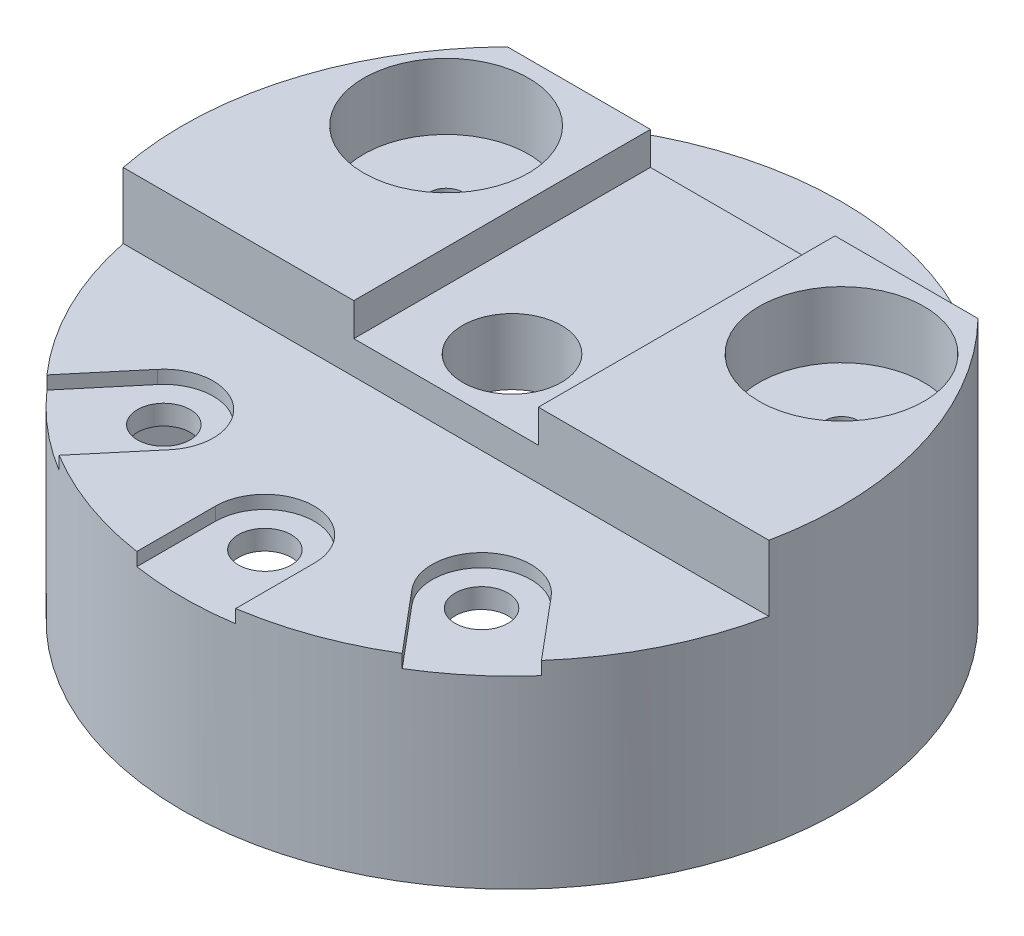
SolidWorks part; units mm, degrees
material "ABS PC"
ref_plane "Front Plane" through (0, 0, 0) normal (0, 0, 1) x (1, 0, 0)
ref_plane "Top Plane" through (0, 0, 0) normal (0, 1, 0) x (1, 0, 0)
ref_plane "Right Plane" through (0, 0, 0) normal (1, 0, 0) x (0, 0, -1)
sketch "Sketch1" plane through (0, 0, 0) normal (0, 1, 0) x (1, 0, 0)
  circle A0 centre (0, 0) radius 5
  circle A1 centre (0, 0) radius 4.75
  dimension "D1" = 10
  dimension "D2" = 0.25
extrude "Boss-Extrude1" add sketch "Sketch1" along normal blind 3
sketch "Sketch2" plane through (0, 3, 0) normal (0, 1, 0) x (1, 0, 0)
  circle A0 centre (0, 0) radius 5 construction
  circle A1 centre (0, 0) radius 5
  circle A2 centre (0, 0) radius 0.75
  dimension "D1" = 1.5
extrude "Boss-Extrude2" add sketch "Sketch2" against normal blind 0.5
sketch "Sketch3" plane through (0, 3, 0) normal (0, 1, 0) x (1, 0, 0)
  line L0 (-4.899, -1) -> (4.899, -1)
  line L1 (0, 0) -> (0, 5) construction
  line L2 (0, 0) -> (-5, 0) construction
  line L3 (-3.5707, 3.5) -> (3.5707, 3.5)
  circle A0 centre (0, 0) radius 5 construction
  circle A1 centre (0, 0) radius 0.75 construction
  circle A2 centre (0, 0) radius 0.75
  circle A3 centre (3, 2) radius 1.25
  circle A4 centre (-3, 2) radius 1.25
  arc A5 (-4.899, -1) -> (-3.5707, 3.5) centre (0, 0) cw
  arc A6 (4.899, -1) -> (3.5707, 3.5) centre (0, 0) ccw
  dimension "D2" = 3.5
  dimension "D3" = 2.5
  dimension "D4" = 2
  dimension "D1" = 1
  dimension "D5" = 3
extrude "Boss-Extrude3" add sketch "Sketch3" along normal blind 1
sketch "Sketch4" plane through (0, 3, 0) normal (0, 1, 0) x (1, 0, 0)
  circle A0 centre (-3, 2) radius 1.25 construction
  circle A1 centre (3, 2) radius 1.25 construction
  circle A2 centre (-3, 2) radius 1.25 construction
  circle A3 centre (3, 2) radius 1.25 construction
  circle A4 centre (-3, 2) radius 0.25
  circle A5 centre (3, 2) radius 0.25
  dimension "D1" = 0.5
  dimension "D2" = 0.5
extrude "Cut-Extrude1" cut sketch "Sketch4" against normal up to surface (0.5 mm away) up to face at (0, 2.5, 0.75)
sketch "Sketch5" plane through (0, 4, 0) normal (0, 1, 0) x (1, 0, 0)
  line L0 (3.5707, 3.5) -> (-3.5707, 3.5) construction
  line L1 (-1.4, 3.5) -> (1.4, 3.5)
  line L2 (-1.4, 3.5) -> (-1.4, -1)
  line L3 (-1.4, -1) -> (1.4, -1)
  line L4 (1.4, 3.5) -> (1.4, -1)
  line L5 (-1.4, 3.5) -> (1.4, -1) construction
  line L6 (-1.4, -1) -> (1.4, 3.5) construction
  line L7 (-4.899, -1) -> (4.899, -1) construction
  point P0 (0, 1.25)
  dimension "D1" = 1.4
extrude "Cut-Extrude2" cut sketch "Sketch5" against normal blind 0.5
sketch "Sketch6" plane through (0, 3, 0) normal (0, 1, 0) x (1, 0, 0)
  line L0 (0, 0) -> (0, -3.75) construction
  line L1 (0, 0) -> (-2.4105, -2.8727) construction
  line L2 (0, 0) -> (2.4105, -2.8727) construction
  circle A0 centre (0, 0) radius 3.75 construction
  circle A1 centre (0, -3.75) radius 0.4
  circle A2 centre (2.4105, -2.8727) radius 0.4
  circle A3 centre (-2.4105, -2.8727) radius 0.4
  dimension "D1" = 7.5
  dimension "D2" = 0.8
  dimension "D3" = 0.8
  dimension "D4" = 0.8
  dimension "D5" = 40
extrude "Cut-Extrude3" cut sketch "Sketch6" against normal up to surface (0.5 mm away) up to face at (3, 2.5, -1.75)
sketch "Sketch7" plane through (0, 3, 0) normal (0, 1, 0) x (1, 0, 0)
  line L0 (-0.75, -3.75) -> (-0.75, -5.45)
  line L1 (-0.75, -5.45) -> (0.75, -5.45)
  line L2 (0.75, -5.45) -> (0.75, -3.75)
  line L3 (0.75, -3.75) -> (-0.75, -3.75) construction
  line L4 (0, 0) -> (-2.4105, -2.8727) construction
  line L5 (2.4105, -2.8727) -> (0, 0) construction
  line L6 (-2.9287, -4.657) -> (-1.8359, -3.3548)
  line L7 (-2.9287, -4.657) -> (-4.0777, -3.6929)
  line L8 (-1.8359, -3.3548) -> (-2.985, -2.3906) construction
  line L9 (-4.0777, -3.6929) -> (-2.985, -2.3906)
  line L10 (2.985, -2.3906) -> (4.0777, -3.6929)
  line L11 (2.985, -2.3906) -> (1.8359, -3.3548) construction
  line L12 (4.0777, -3.6929) -> (2.9287, -4.657)
  line L13 (1.8359, -3.3548) -> (2.9287, -4.657)
  arc A0 (-0.75, -3.75) -> (0.75, -3.75) centre (0, -3.75) cw
  arc A1 (-2.985, -2.3906) -> (-1.8359, -3.3548) centre (-2.4105, -2.8727) cw
  circle A2 centre (2.4105, -2.8727) radius 0.4 construction
  circle A3 centre (-2.4105, -2.8727) radius 0.4 construction
  circle A4 centre (2.4105, -2.8727) radius 0.4
  circle A5 centre (-2.4105, -2.8727) radius 0.4
  circle A6 centre (0, -3.75) radius 0.4 construction
  circle A7 centre (0, -3.75) radius 0.4
  arc A8 (1.8359, -3.3548) -> (2.985, -2.3906) centre (2.4105, -2.8727) cw
  dimension "D2" = 1.5
  dimension "D1" = 1.7
extrude "Cut-Extrude4" cut sketch "Sketch7" against normal blind 0.2
